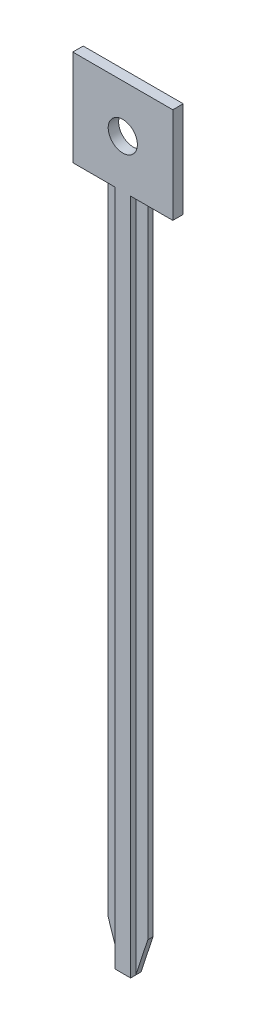
SolidWorks part; units mm, degrees
ref_plane "Front Plane" through (0, 0, 0) normal (0, 0, 1) x (1, 0, 0)
ref_plane "Top Plane" through (0, 0, 0) normal (0, 1, 0) x (1, 0, 0)
ref_plane "Right Plane" through (0, 0, 0) normal (1, 0, 0) x (0, 0, -1)
sketch "Sketch1" plane through (0, 0, 0) normal (0, 0, 1) x (1, 0, 0)
  line L0 (0, 0) -> (12.192, 0)
  line L1 (12.192, 0) -> (12.192, -11.684)
  line L2 (0, -11.684) -> (3.683, -11.684)
  line L3 (0, -11.684) -> (0, 0)
  line L5 (7.0485, -94.234) -> (5.1435, -94.234)
  line L7 (3.683, -11.684) -> (3.683, -89.789)
  line L8 (12.192, -11.684) -> (8.509, -11.684)
  line L9 (8.509, -11.684) -> (8.509, -89.789)
  line L10 (5.1435, -94.234) -> (3.683, -89.789)
  line L11 (7.0485, -94.234) -> (8.509, -89.789)
  line L12 (7.0485, -94.234) -> (7.0485, -89.789) construction
  dimension "D1" = 12.192
  dimension "D2" = 11.684
  dimension "D3" = 78.105
  dimension "D4" = 3.683
  dimension "D5" = 18.189
  dimension "D6" = 82.55
extrude "Boss-Extrude1" add sketch "Sketch1" along normal blind 1.27
ref_plane "Plane1" through (0, 0, 1.27) normal (0, 0, 1) x (1, 0, 0)
sketch "Sketch2" plane through (0, 0, 1.27) normal (0, 0, 1) x (1, 0, 0)
  line L0 (5.1435, -94.234) -> (5.1435, -11.684)
  line L1 (5.1435, -11.684) -> (3.683, -11.684)
  line L2 (3.683, -11.684) -> (3.683, -89.789)
  line L3 (3.683, -89.789) -> (5.1435, -94.234)
  line L4 (8.509, -11.684) -> (8.509, -89.789)
  line L5 (8.509, -89.789) -> (7.0485, -94.234)
  line L6 (7.0485, -94.234) -> (7.0485, -11.684)
  line L7 (7.0485, -11.684) -> (8.509, -11.684)
extrude "Cut-Extrude1" cut sketch "Sketch2" against normal blind 0.635
sketch "Sketch3" plane through (0, 0, 1.27) normal (0, 0, 1) x (1, 0, 0)
  line L0 (0, 0) -> (0, -11.684) construction
  line L2 (12.192, 0) -> (0, 0) construction
  circle A0 centre (6.096, -5.842) radius 1.778
  dimension "D1" = 3.556
  dimension "D2" = 6.096
  dimension "D3" = 5.842
extrude "Cut-Extrude2" cut sketch "Sketch3" against normal through all
